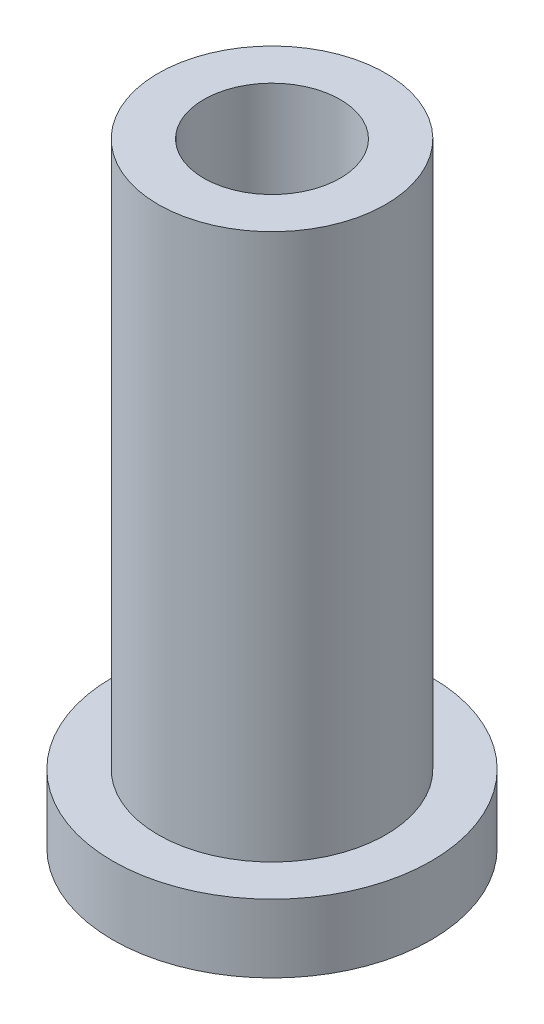
SolidWorks part; units mm, degrees
ref_plane "Plan de face" through (0, 0, 0) normal (0, 0, 1) x (1, 0, 0)
ref_plane "Plan de dessus" through (0, 0, 0) normal (0, 1, 0) x (1, 0, 0)
ref_plane "Plan de droite" through (0, 0, 0) normal (1, 0, 0) x (0, 0, -1)
sketch "Esquisse1" plane through (0, 0, 0) normal (0, 0, 1) x (1, 0, 0)
  line L0 (0, 18.3415) -> (0, -23.7073) construction
  line L1 (6, 40.3415) -> (6, -13.6585)
  line L2 (6, -13.6585) -> (14, -13.6585)
  line L3 (14, -13.6585) -> (14, -7.6585)
  line L4 (14, -7.6585) -> (10, -7.6585)
  line L5 (10, -7.6585) -> (10, 40.3415)
  line L6 (10, 40.3415) -> (6, 40.3415)
  dimension "D1" = 4
  dimension "D2" = 48
  dimension "D3" = 54
  dimension "D4" = 4
  dimension "D5" = 10
revolve "Révolution1" add sketch "Esquisse1" angle 360 about L0
